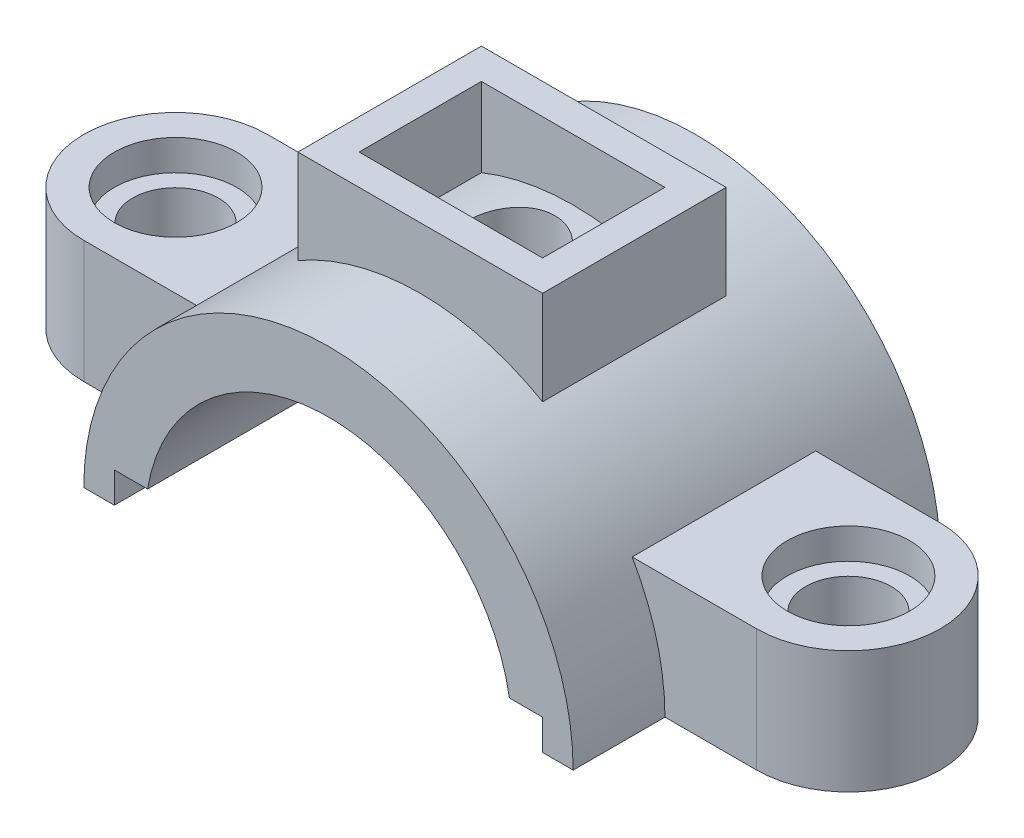
SolidWorks part; units mm, degrees
ref_plane "Front Plane" through (0, 0, 0) normal (0, 0, 1) x (1, 0, 0)
ref_plane "Top Plane" through (0, 0, 0) normal (0, 1, 0) x (1, 0, 0)
ref_plane "Right Plane" through (0, 0, 0) normal (1, 0, 0) x (0, 0, -1)
sketch "Sketch1" plane through (0, 0, 0) normal (0, 1, 0) x (1, 0, 0)
  line L0 (-55, 0) -> (55, 0) construction
  line L1 (-55, 15) -> (55, 15)
  line L2 (-55, -15) -> (55, -15)
  arc A0 (-55, 15) -> (-55, -15) centre (-55, 0) ccw
  arc A1 (55, -15) -> (55, 15) centre (55, 0) ccw
  point P2 (0, 0)
  dimension "D2" = 15
  dimension "D1" = 110
extrude "Boss-Extrude1" add sketch "Sketch1" along normal blind 20 contours L1 A1 L2 A0
sketch "Sketch2" plane through (0, 0, 0) normal (0, 0, 1) x (1, 0, 0)
  line L0 (-55, 0) -> (55, 0) construction
  line L1 (-40, 0) -> (40, 0)
  arc A0 (40, 0) -> (-40, 0) centre (0, 0) ccw
  dimension "D1" = 40
extrude "Boss-Extrude2" add sketch "Sketch2" along normal mid plane 60
ref_plane "Plane1" through (0, 50, 0) normal (0, 1, 0) x (1, 0, 0)
sketch "Sketch3" plane through (0, 50, 0) normal (0, 1, 0) x (1, 0, 0)
  line L1 (-15, 10) -> (15, 10)
  line L2 (-15, 10) -> (-15, -10)
  line L3 (-15, -10) -> (15, -10)
  line L4 (15, 10) -> (15, -10)
  line L5 (-15, 10) -> (15, -10) construction
  line L6 (-15, -10) -> (15, 10) construction
  line L7 (-20, 15) -> (20, 15)
  line L8 (-20, 15) -> (-20, -15)
  line L9 (-20, -15) -> (20, -15)
  line L10 (20, 15) -> (20, -15)
  line L11 (-20, 15) -> (20, -15) construction
  line L12 (-20, -15) -> (20, 15) construction
  point P0 (0, 0)
  point P6 (0, 0)
  dimension "D1" = 30
  dimension "D2" = 40
  dimension "D3" = 30
  dimension "D4" = 20
extrude "Boss-Extrude3" add sketch "Sketch3" against normal up to next
sketch "Sketch4" plane through (0, 0, 30) normal (0, 0, 1) x (1, 0, 0)
  line L0 (-40, 0) -> (40, 0) construction
  line L1 (-30, 0) -> (30, 0)
  arc A0 (30, 0) -> (-30, 0) centre (0, 0) ccw
  point P6 (0, 0)
  dimension "D1" = 30
extrude "Cut-Extrude1" cut sketch "Sketch4" along normal through all and the other way through all
sketch "Sketch5" plane through (0, 0, 30) normal (0, 0, 1) x (1, 0, 0)
  line L0 (-40, 0) -> (-30, 0) construction
  line L1 (-35, 0) -> (35, 0)
  line L2 (-35, 0) -> (-35, 5)
  line L3 (-35, 5) -> (35, 5)
  line L4 (35, 0) -> (35, 5)
  line L5 (0, 0) -> (0, 18.2789) construction
  dimension "D1" = 5
extrude "Cut-Extrude2" cut sketch "Sketch5" against normal through all
sketch "Sketch11" plane through (0, 50, 0) normal (0, 1, 0) x (1, 0, 0)
  point P0 (0, 0)
  point P3 (0, 0)
hole_wizard "Hole1" positions "Sketch11" profile "Sketch10" legacy end condition through all
sketch "Sketch10" plane through (0, 50, 0) normal (1, 0, 0) x (0, 0, 1)
  line L0 (0, 0) -> (0, 50)
  line L1 (0, 50) -> (7, 50)
  line L2 (7, 50) -> (7, 0)
  line L3 (7, 0) -> (0, 0)
  line L4 (0, 110) -> (0, -10) construction
  dimension "Diameter" = 14
  dimension "Depth" = 50
sketch "Sketch14" plane through (0, 20, 0) normal (0, 1, 0) x (1, 0, 0)
  point P0 (-55, 0)
  point P3 (55, 0)
sketch "Sketch17" plane through (0, 20, 0) normal (0, 1, 0) x (1, 0, 0)
  point P0 (-55, 0)
  point P3 (55, 0)
hole_wizard "Hole3" positions "Sketch17" profile "Sketch16" legacy end condition through all
sketch "Sketch16" plane through (-55, 20, 0) normal (1, 0, 0) x (0, 0, 1)
  line L0 (0, 0) -> (0, 24.206)
  line L1 (0, 24.206) -> (7, 20)
  line L2 (7, 20) -> (7, 5)
  line L3 (7, 5) -> (10, 5)
  line L4 (10, 0) -> (0, 0)
  line L5 (0, -11.3109) -> (0, 121.1557) construction
  line L6 (0, 24.206) -> (-7, 20) construction
  line L7 (10, 5) -> (10, 0)
  dimension "Depth" = 20
  dimension "Drill Angle" = 118
  dimension "Diameter" = 14
  dimension "C-Bore Diameter" = 20
  dimension "C-Bore Depth" = 5
